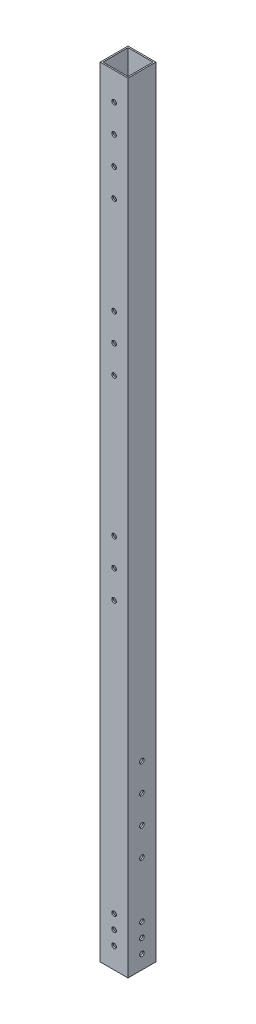
SolidWorks part; units mm, degrees
ref_plane "前视基准面" through (0, 0, 0) normal (0, 0, 1) x (1, 0, 0)
ref_plane "上视基准面" through (0, 0, 0) normal (0, 1, 0) x (1, 0, 0)
ref_plane "右视基准面" through (0, 0, 0) normal (1, 0, 0) x (0, 0, -1)
other "Configuration Table"
sketch "草图1" plane through (0, 0, 0) normal (0, 1, 0) x (1, 0, 0)
  line L9 (-9, 9) -> (9, 9)
  line L10 (-9, 9) -> (-9, -9)
  line L11 (-9, -9) -> (9, -9)
  line L12 (9, 9) -> (9, -9)
  line L13 (-9, 9) -> (9, -9) construction
  line L14 (-9, -9) -> (9, 9) construction
  line L15 (-10, 10) -> (10, 10)
  line L16 (-10, 10) -> (-10, -10)
  line L17 (-10, -10) -> (10, -10)
  line L18 (10, 10) -> (10, -10)
  line L19 (-10, 10) -> (10, -10) construction
  line L20 (-10, -10) -> (10, 10) construction
  point P0 (0, 0)
  point P6 (0, 0)
  dimension "D1" = 18
  dimension "D2" = 18
  dimension "D3" = 20
  dimension "D4" = 20
extrude "凸台-拉伸1" add sketch "草图1" along normal blind 740
sketch "草图3" plane through (0, 0, 10) normal (0, 0, 1) x (1, 0, 0)
  line L0 (0, 740) -> (0, 720) construction
  line L1 (-10, 740) -> (10, 740) construction
  line L2 (0, 720) -> (0, 700) construction
  line L3 (0, 700) -> (0, 680) construction
  line L4 (0, 680) -> (0, 660) construction
  circle A0 centre (0, 720) radius 1.65
  circle A1 centre (0, 700) radius 1.65
  circle A2 centre (0, 680) radius 1.65
  circle A3 centre (0, 660) radius 1.65
  circle A4 centre (0, 590) radius 1.65
  circle A5 centre (0, 570) radius 1.65
  circle A6 centre (0, 550) radius 1.65
  circle A7 centre (0, 450) radius 1.65
  circle A8 centre (0, 430) radius 1.65
  circle A9 centre (0, 410) radius 1.65
  dimension "D5" = 3.3
  dimension "D6" = 3.3
  dimension "D7" = 3.3
  dimension "D8" = 3.3
  dimension "D10" = 3.3
  dimension "D11" = 3.3
  dimension "D14" = 3.3
  dimension "D18" = 3.3
  dimension "D19" = 3.3
  dimension "D20" = 3.3
  dimension "D1" = 20
  dimension "D2" = 20
  dimension "D3" = 20
  dimension "D4" = 20
  dimension "D9" = 150
  dimension "D12" = 20
  dimension "D13" = 20
  dimension "D15" = 20
  dimension "D16" = 20
  dimension "D17" = 100
extrude "切除-拉伸1" cut sketch "草图3" against normal blind 32
sketch "草图4" plane through (10, 0, 0) normal (1, 0, 0) x (0, 0, -1)
  line L0 (0, 0) -> (0, 250) construction
  circle A0 centre (0, 250) radius 1.65
  circle A1 centre (0, 270) radius 1.65
  circle A2 centre (0, 290) radius 1.65
  circle A3 centre (0, 310) radius 1.65
  dimension "D2" = 3.3
  dimension "D1" = 250
  dimension "D3" = 4
extrude "切除-拉伸2" cut sketch "草图4" against normal through all
sketch "草图5" plane through (0, 0, 0) normal (0, -1, 0) x (1, 0, 0)
  circle A0 centre (0, 0) radius 14.5662
extrude "切除-拉伸3" cut sketch "草图5" against normal blind 180
sketch "草图6" plane through (10, 0, 0) normal (1, 0, 0) x (0, 0, -1)
  circle A0 centre (0, 190) radius 1.65
  circle A1 centre (0, 200) radius 1.65
  circle A2 centre (0, 210) radius 1.65
  dimension "D1" = 3.3
  dimension "D2" = 3
extrude "切除-拉伸4" cut sketch "草图6" against normal blind 30
sketch "草图7" plane through (0, 0, -10) normal (0, 0, -1) x (-1, 0, 0)
  line L0 (10, 180) -> (-10, 180) construction
  circle A0 centre (0, 195) radius 1.65
  circle A1 centre (0, 205) radius 1.65
  circle A2 centre (0, 215) radius 1.65
  dimension "D1" = 3.3
  dimension "D2" = 3.3
  dimension "D3" = 3.3
  dimension "D4" = 15
  dimension "D5" = 10
  dimension "D6" = 10
extrude "切除-拉伸5" cut sketch "草图7" against normal through all
